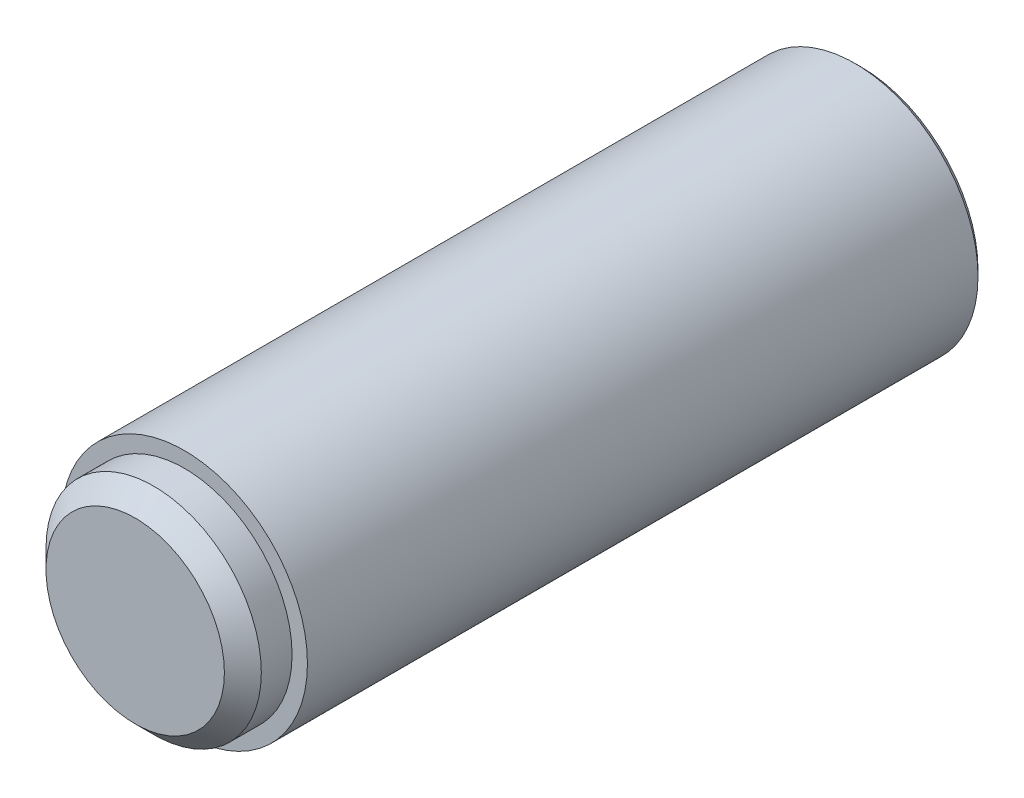
SolidWorks part; units mm, degrees
material "45"
ref_plane "前视基准面" through (0, 0, 0) normal (0, 0, 1) x (1, 0, 0)
ref_plane "上视基准面" through (0, 0, 0) normal (0, 1, 0) x (1, 0, 0)
ref_plane "右视基准面" through (0, 0, 0) normal (1, 0, 0) x (0, 0, -1)
sketch "草图1" plane through (0, 0, 0) normal (0, 0, 1) x (1, 0, 0)
  circle A0 centre (0, 0) radius 20
  dimension "D1" = 40
extrude "凸台-拉伸1" add sketch "草图1" along normal blind 110
sketch "草图2" plane through (0, 0, 110) normal (0, 0, 1) x (1, 0, 0)
  circle A0 centre (0, 0) radius 17.5
  circle A1 centre (0, 0) radius 20 construction
  dimension "D1" = 35
extrude "凸台-拉伸2" add sketch "草图2" along normal blind 8
chamfer "倒角1" distance 3 angle 45 1 edges at (17.5, 0, 118)
chamfer "倒角2" distance 1 angle 45 1 edges at (20, 0, 0)
